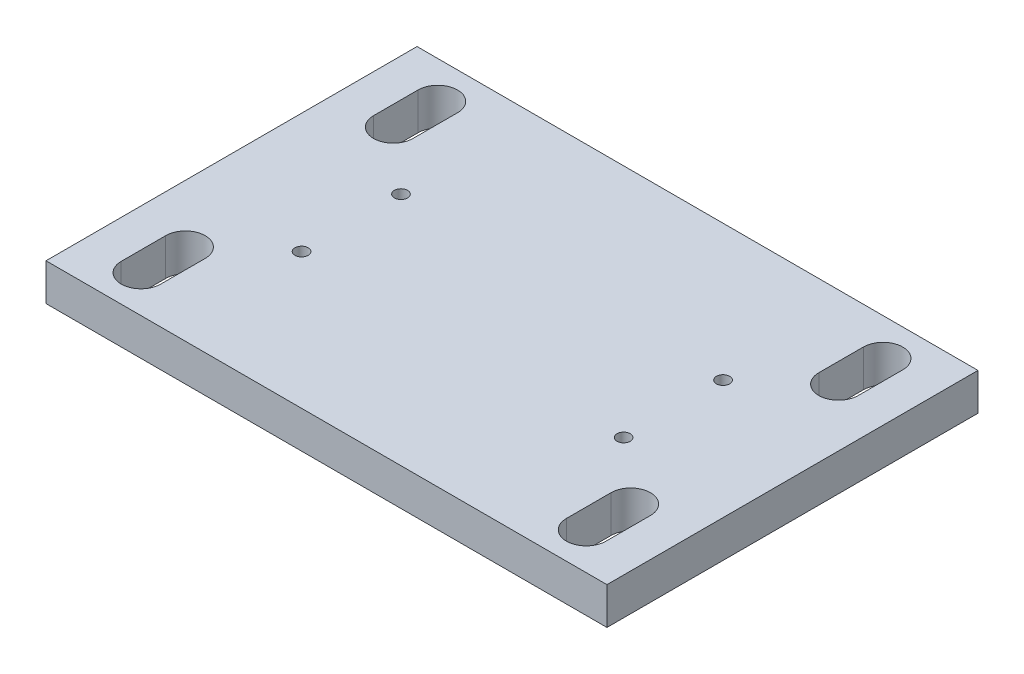
SolidWorks part; units mm, degrees
ref_plane "Front Plane" through (0, 0, 0) normal (0, 0, 1) x (1, 0, 0)
ref_plane "Top Plane" through (0, 0, 0) normal (0, 1, 0) x (1, 0, 0)
ref_plane "Right Plane" through (0, 0, 0) normal (1, 0, 0) x (0, 0, -1)
sketch "Sketch1" plane through (0, 0, 0) normal (0, 1, 0) x (1, 0, 0)
  line L1 (-48, 31.75) -> (48, 31.75)
  line L2 (-48, 31.75) -> (-48, -31.75)
  line L3 (-48, -31.75) -> (48, -31.75)
  line L4 (48, 31.75) -> (48, -31.75)
  point P4 (48, 0)
  point P6 (0, 31.75)
  dimension "D1" = 96
  dimension "D2" = 63.5
extrude "Mount Block" add sketch "Sketch1" along normal blind 6.35
hole_wizard "Linear Stage #4-40 Tapped Hole" positions "Sketch2" profile "Sketch3" tap size "#4-40" standard "ANSI Inch" end condition through all
sketch "Sketch2" plane through (0, 6.35, 0) normal (0, 1, 0) x (1, 0, 0)
  point P0 (-27.5, 8.5)
  point P10 (27.618, 8.5)
  point P11 (27.618, -8.518)
  point P12 (-27.5, -8.518)
  dimension "D3" = 8.5
  dimension "D4" = 27.5
  dimension "D1" = 2
  dimension "D2" = 2
sketch "Sketch3" plane through (-27.5, 6.35, -8.5) normal (1, 0, 0) x (0, 0, 1)
  line L0 (0, 0) -> (0, 6.35)
  line L1 (0, 6.35) -> (1.1303, 6.35)
  line L2 (1.1303, 6.35) -> (1.1303, 0)
  line L5 (1.1303, 0) -> (0, 0)
  line L11 (0, -6.35) -> (0, 107.95) construction
  dimension "Thru Tap Drill Dia." = 2.2606
  dimension "Thru Tap Drill Depth" = 6.35
cosmetic thread "Hole Thread1" parameters "D2"=2.8448
cosmetic thread "Hole Thread2" parameters "D2"=2.8448
cosmetic thread "Hole Thread3" parameters "D2"=2.8448
cosmetic thread "Hole Thread4" parameters "D2"=2.8448
hole_wizard "Optical Table 1/4 (0.25) Diameter Hole" positions "Sketch4" profile "Sketch5" hole size "1/4" standard "ANSI Inch" end condition through all
sketch "Sketch4" plane through (0, 6.35, 0) normal (0, 1, 0) x (1, 0, 0)
  point P0 (-38.1, 25.4)
  point P7 (38.1, 25.4)
  point P8 (38.1, -25.4)
  point P9 (-38.1, -25.4)
  dimension "D3" = 38.1
  dimension "D4" = 25.4
  dimension "D1" = 2
  dimension "D2" = 2
sketch "Sketch5" plane through (-38.1, 6.35, -25.4) normal (1, 0, 0) x (0, 0, 1)
  line L0 (0, 0) -> (0, 6.35)
  line L1 (0, 6.35) -> (3.175, 6.35)
  line L2 (3.175, 6.35) -> (3.175, 0)
  line L5 (3.175, 0) -> (0, 0)
  line L11 (0, -6.35) -> (0, 107.95) construction
  dimension "Thru Hole Dia." = 6.35
  dimension "Thru Hole Depth" = 6.35
sketch "Sketch6" plane through (0, 6.35, 0) normal (0, 1, 0) x (1, 0, 0)
  line L0 (-38.1, 25.4) -> (-38.1, 17.78) construction
  line L1 (-34.7218, 25.4) -> (-34.7218, 17.78)
  line L2 (-41.4782, 25.4) -> (-41.4782, 17.78)
  line L3 (38.1, 25.4) -> (38.1, 17.78) construction
  line L4 (41.4782, 25.4) -> (41.4782, 17.78)
  line L5 (34.7218, 25.4) -> (34.7218, 17.78)
  line L6 (38.1, -17.78) -> (38.1, -25.4) construction
  line L7 (41.4782, -17.78) -> (41.4782, -25.4)
  line L8 (34.7218, -17.78) -> (34.7218, -25.4)
  line L9 (-38.1, -17.78) -> (-38.1, -25.4) construction
  line L10 (-34.7218, -17.78) -> (-34.7218, -25.4)
  line L11 (-41.4782, -17.78) -> (-41.4782, -25.4)
  arc A0 (-34.7218, 25.4) -> (-41.4782, 25.4) centre (-38.1, 25.4) ccw
  arc A1 (-41.4782, 17.78) -> (-34.7218, 17.78) centre (-38.1, 17.78) ccw
  arc A2 (41.4782, 25.4) -> (34.7218, 25.4) centre (38.1, 25.4) ccw
  arc A3 (34.7218, 17.78) -> (41.4782, 17.78) centre (38.1, 17.78) ccw
  arc A4 (41.4782, -17.78) -> (34.7218, -17.78) centre (38.1, -17.78) ccw
  arc A5 (34.7218, -25.4) -> (41.4782, -25.4) centre (38.1, -25.4) ccw
  arc A6 (-34.7218, -17.78) -> (-41.4782, -17.78) centre (-38.1, -17.78) ccw
  arc A7 (-41.4782, -25.4) -> (-34.7218, -25.4) centre (-38.1, -25.4) ccw
  point P3 (-38.1, 21.59)
  point P12 (38.1, 21.59)
  point P19 (38.1, -21.59)
  point P26 (-38.1, -21.59)
  dimension "D1" = 3.3782
  dimension "D2" = 7.62
  dimension "D3" = 2
  dimension "D4" = 2
extrude "Optical Tasble Cut-Extrude" cut sketch "Sketch6" against normal blind 6.35
